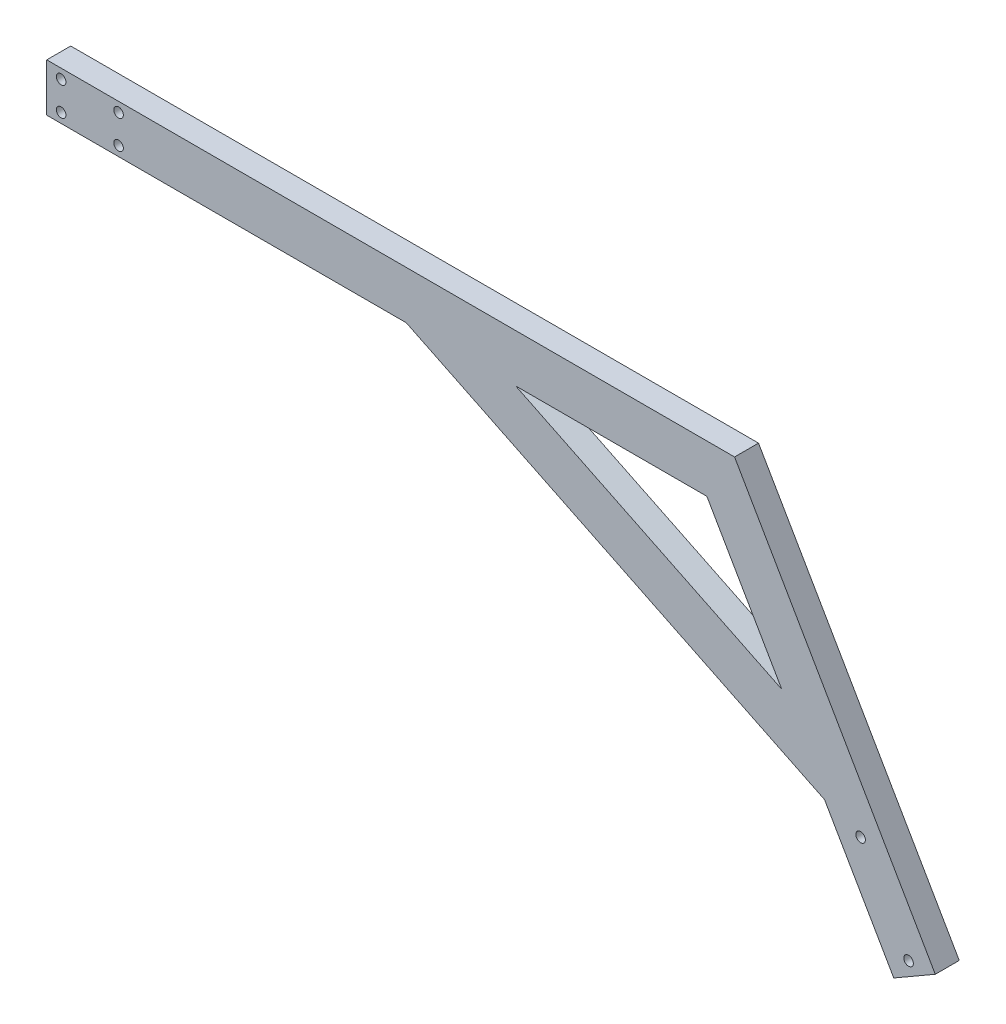
SolidWorks part; units mm, degrees
ref_plane "Front Plane" through (0, 0, 0) normal (0, 0, 1) x (1, 0, 0)
ref_plane "Top Plane" through (0, 0, 0) normal (0, 1, 0) x (1, 0, 0)
ref_plane "Right Plane" through (0, 0, 0) normal (1, 0, 0) x (0, 0, -1)
sketch "Sketch1" plane through (0, 0, 0) normal (0, 0, 1) x (1, 0, 0)
  line L0 (0, 0) -> (275.4, 0)
  line L1 (275.4, 0) -> (353.366, -135.0411)
  line L2 (353.366, -135.0411) -> (370.6865, -125.0411)
  line L3 (370.6865, -125.0411) -> (286.947, 20)
  line L4 (286.947, 20) -> (0, 20)
  line L5 (0, 20) -> (0, 0)
  line L6 (362.0263, -130.0411) -> (339.5263, -91.07) construction
  line L7 (6, 15.98) -> (29.96, 15.98) construction
  line L8 (6, 15.98) -> (6, 4.02) construction
  line L9 (6, 4.02) -> (29.96, 4.02) construction
  line L10 (29.96, 15.98) -> (29.96, 4.02) construction
  circle A0 centre (6, 15.98) radius 2
  circle A1 centre (29.96, 15.98) radius 2
  circle A2 centre (29.96, 4.02) radius 2
  circle A3 centre (6, 4.02) radius 2
  circle A4 centre (339.5263, -91.07) radius 2
  circle A5 centre (359.5263, -125.711) radius 2
  point P11 (6, 10)
  point P12 (0, 10)
  point P23 (0, 0)
  point P24 (0, 0)
  point P25 (218.8413, -56.2597)
  dimension "D9" = 4
  dimension "D10" = 4
  dimension "D1" = 20
  dimension "D2" = 20
  dimension "D3" = 120
  dimension "D4" = 91.07
  dimension "D5" = 275.4
  dimension "D6" = 23.96
  dimension "D7" = 11.96
  dimension "D8" = 6
  dimension "D11" = 40
  dimension "D12" = 5
extrude "Boss-Extrude1" add sketch "Sketch1" along normal blind 10
sketch "Sketch2" plane through (0, 0, 0) normal (0, 0, 1) x (1, 0, 0)
  line L0 (150, 0) -> (324.4985, -85.0411)
  line L1 (0, 0) -> (275.4, 0) construction
  line L2 (275.4, 0) -> (353.366, -135.0411) construction
  line L3 (150, 0) -> (195.6527, 0)
  line L4 (195.6527, 0) -> (306.6239, -54.0814)
  line L5 (306.6239, -54.0814) -> (324.4985, -85.0411)
  point P11 (327.0214, -85.0411)
  point P12 (195.6527, -0.3196)
  point P13 (0, 0)
  point P14 (150.591, 0)
  dimension "D1" = 20
  dimension "D2" = 50
  dimension "D3" = 150
extrude "Boss-Extrude2" add sketch "Sketch2" along normal blind 10
